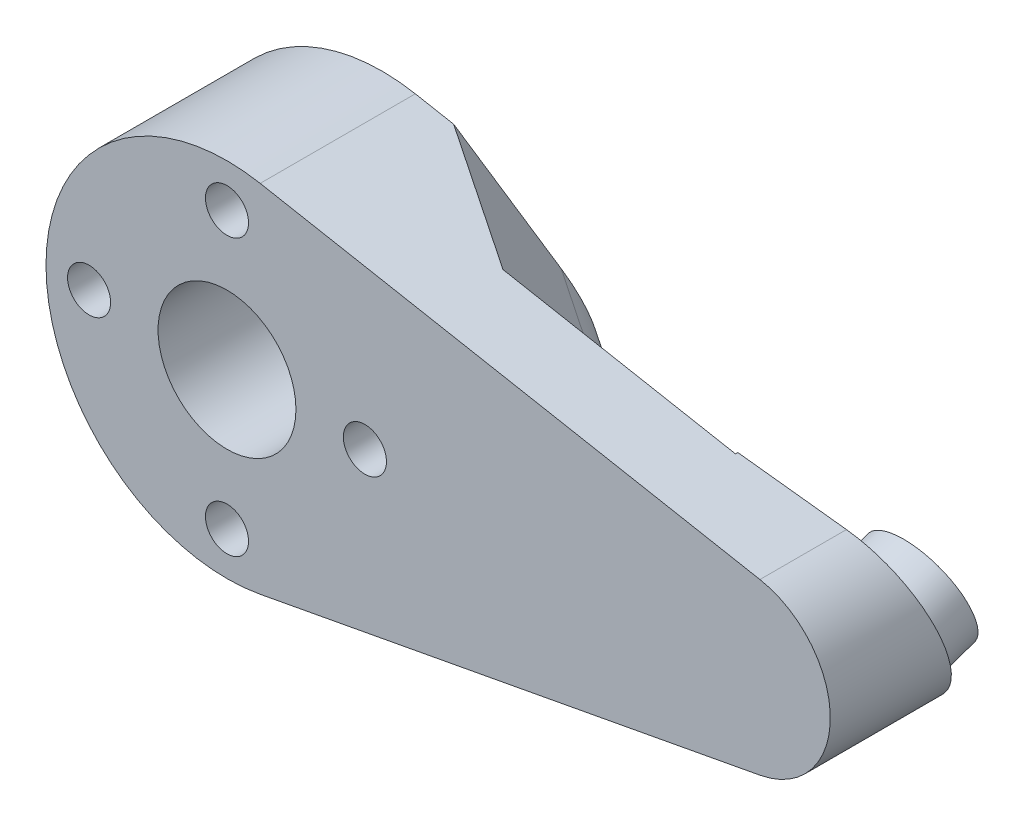
SolidWorks part; units mm, degrees
ref_plane "Plan de face" through (0, 0, 0) normal (0, 0, 1) x (1, 0, 0)
ref_plane "Plan de dessus" through (0, 0, 0) normal (0, 1, 0) x (1, 0, 0)
ref_plane "Plan de droite" through (0, 0, 0) normal (1, 0, 0) x (0, 0, -1)
sketch "Esquisse1" plane through (0, 0, 0) normal (0, 0, 1) x (1, 0, 0)
  line L0 (1.925, 10.322) -> (30.9167, 4.9153)
  line L1 (30.9167, -4.9153) -> (1.925, -10.322)
  arc A0 (1.925, 10.322) -> (1.925, -10.322) centre (0, 0) ccw
  arc A1 (30.9167, 4.9153) -> (30.9167, -4.9153) centre (30, 0) cw
  dimension "D1" = 10.5
  dimension "D2" = 5
  dimension "D3" = 30
extrude "Boss.-Extru.1" add sketch "Esquisse1" along normal blind 10
sketch "Esquisse2" plane through (0, 0, 10) normal (0, 0, 1) x (1, 0, 0)
  circle A0 centre (0, 0) radius 4
  circle A1 centre (0, 8) radius 1.25
  circle A2 centre (8, 0) radius 1.25
  circle A3 centre (0, -8) radius 1.25
  circle A4 centre (-8, 0) radius 1.25
  point P14 (0, 0)
  dimension "D1" = 2.5
  dimension "D2" = 8
  dimension "D3" = 8
  dimension "D4" = 4
extrude "Enlèv. mat.-Extru.1" cut sketch "Esquisse2" against normal up to next
sketch "Esquisse4" plane through (0, 0, 0) normal (0, 1, 0) x (1, 0, 0)
  line L0 (20, -5.5) -> (25, -5.5)
  line L1 (25, -5.5) -> (25, 0)
  line L2 (25, 0) -> (11, 0)
  line L3 (11, 0) -> (20, -5.5)
  line L4 (30.9167, 0) -> (1.925, 0) construction
  dimension "D1" = 11
  dimension "D2" = 9
  dimension "D3" = 5
  dimension "D4" = 5.5
extrude "Enlèv. mat.-Extru.2" cut sketch "Esquisse4" against normal up to next and the other way up to next
sketch "Esquisse5" plane through (0, 0, 0) normal (0, 0, -1) x (-1, 0, 0)
  line L3 (-25, -6.0187) -> (-25, 6.0187)
  line L4 (-25, 6.0187) -> (-30.9167, 4.9153)
  line L5 (-30.9167, -4.9153) -> (-25, -6.0187)
  line L6 (-25, -6.0187) -> (-25, 6.0187)
  line L7 (-25, 6.0187) -> (-30.9167, 4.9153)
  line L8 (-30.9167, -4.9153) -> (-25, -6.0187)
  arc A1 (-30.9167, 4.9153) -> (-30.9167, -4.9153) centre (-30, 0) ccw
  arc A2 (-30.9167, 4.9153) -> (-30.9167, -4.9153) centre (-30, 0) ccw
  dimension "D1" = 0
extrude "Boss.-Extru.2" add sketch "Esquisse5" along normal blind 2
sketch "Esquisse6" plane through (25, 0, 0) normal (-1, 0, 0) x (0, 0, 1)
  line L4 (-2, -6.0187) -> (2.1871, 6.0187)
  line L5 (-2, 6.0187) -> (5.5, 6.0187) construction
  line L6 (2.1871, 6.0187) -> (-2, 6.0187)
  line L7 (-2, 6.0187) -> (-2, -6.0187)
  dimension "D1" = 19.18
extrude "Enlèv. mat.-Extru.3" cut sketch "Esquisse6" against normal up to next
sketch "Esquisse7" plane through (0, -0.029, 0.0835) normal (0, 0.3285, -0.9445) x (-1, 0, 0)
  line L0 (8, 0) -> (-34.9999, 0) construction
  line L1 (-25, -6.3417) -> (-25, 6.4031) construction
  circle A0 centre (-30, -1.1319) radius 1.25
  ellipse E0 centre (8, 0) end of major axis (6.75, 0) minor radius 1.1806 construction
  ellipse E1 centre (-8, 0) end of major axis (-9.25, 0) minor radius 1.1806 construction
  ellipse E2 centre (8, 0) end of major axis (6.75, 0) minor radius 1.1806 construction
  ellipse E3 centre (-8, 0) end of major axis (-6.75, 0) minor radius 1.1806 construction
  ellipse E4 centre (-30, 0.0307) end of major axis (-30, -5.2631) minor radius 5 (-29.258, -5.2045) -> (-29.258, 5.266) ccw construction
  dimension "D2" = 2.5
  dimension "D1" = 5
  dimension "D3" = 1.1319
extrude "Enlèv. mat.-Extru.4" cut sketch "Esquisse7" against normal blind 6
sketch "Esquisse8" plane through (0, -0.029, 0.0835) normal (0, 0.3285, -0.9445) x (-1, 0, 0)
  line L0 (-25, -10.8272) -> (-25, 10.9138)
  line L1 (-25, 10.9138) -> (-38.8482, 10.9138)
  line L2 (-38.8482, 10.9138) -> (-38.8482, -10.8272)
  line L3 (-38.8482, -10.8272) -> (-25, -10.8272)
  line L4 (-25, -6.3417) -> (-25, 6.4031) construction
extrude "Enlèv. mat.-Extru.5" cut sketch "Esquisse8" against normal blind 3
sketch "Esquisse9" plane through (0, -1.0146, 2.9169) normal (0, 0.3285, -0.9445) x (-1, 0, 0)
  line L1 (-30.9167, -4.1299) -> (-25, -5.2981) construction
  circle A0 centre (-30, -1.1319) radius 3.1187
  circle A1 centre (-30, -1.1319) radius 1.25 construction
  circle A2 centre (-30, -1.1319) radius 1.25
extrude "Boss.-Extru.3" add sketch "Esquisse9" along normal blind 3
chamfer "Chanfrein1" distance 4 angle 45 2 edges at (15.5, 7.7904, 2.75) (15.5, -7.7904, 2.75)
fillet "Congé1" radius 4 3 edges at (15.5, 3.74, 2.75) (15.5, -3.2891, 2.75) (25, -6.0187, 3.3382)
sketch "Esquisse10" plane through (0, 0, 0) normal (0, 0, -1) x (-1, 0, 0)
  circle A0 centre (0, 0) radius 15.6318
extrude "Enlèv. mat.-Extru.6" cut sketch "Esquisse10" against normal blind 1
